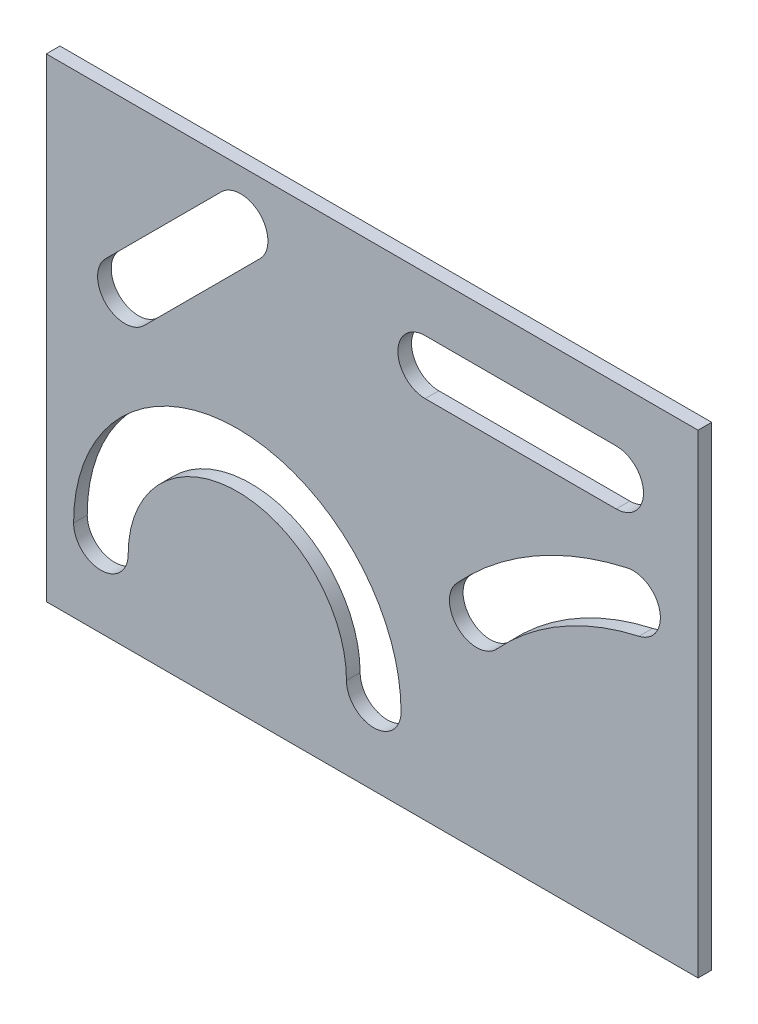
SolidWorks part; units mm, degrees
ref_plane "Front Plane" through (0, 0, 0) normal (0, 0, 1) x (1, 0, 0)
ref_plane "Top Plane" through (0, 0, 0) normal (0, 1, 0) x (1, 0, 0)
ref_plane "Right Plane" through (0, 0, 0) normal (1, 0, 0) x (0, 0, -1)
other "Configuration Table"
sketch "Sketch1" plane through (0, 0, 0) normal (0, 0, 1) x (1, 0, 0)
  line L1 (-238.8352, -173.858) -> (238.8352, -173.858)
  line L2 (-238.8352, -173.858) -> (-238.8352, 173.858)
  line L3 (-238.8352, 173.858) -> (238.8352, 173.858)
  line L4 (238.8352, -173.858) -> (238.8352, 173.858)
  line L5 (-238.8352, -173.858) -> (238.8352, 173.858) construction
  line L6 (-238.8352, 173.858) -> (238.8352, -173.858) construction
  point P0 (0, 0)
extrude "Boss-Extrude1" add sketch "Sketch1" along normal blind 10
sketch "Sketch2" plane through (0, 0, 10) normal (0, 0, 1) x (1, 0, 0)
  line L0 (-181.2616, 51.4316) -> (-96.4088, 136.2844) construction
  line L1 (-195.4037, 65.5737) -> (-110.5509, 150.4265)
  line L2 (-167.1194, 37.2894) -> (-82.2666, 122.1422)
  line L3 (38.8352, 113.858) -> (178.8352, 113.858) construction
  line L4 (38.8352, 133.858) -> (178.8352, 133.858)
  line L5 (38.8352, 93.858) -> (178.8352, 93.858)
  line L6 (238.8352, -173.858) -> (128.8352, 16.6676) construction
  line L7 (238.8352, -173.858) -> (238.8352, 173.858) construction
  line L8 (-198.8352, -113.858) -> (1.1648, -113.858) construction
  line L9 (-238.8352, 173.858) -> (-238.8352, -173.858) construction
  line L10 (-238.8352, -173.858) -> (238.8352, -173.858) construction
  line L12 (238.8352, 173.858) -> (-238.8352, 173.858) construction
  arc A0 (-195.4037, 65.5737) -> (-167.1194, 37.2894) centre (-181.2616, 51.4316) ccw
  arc A1 (-82.2666, 122.1422) -> (-110.5509, 150.4265) centre (-96.4088, 136.2844) ccw
  arc A2 (38.8352, 133.858) -> (38.8352, 93.858) centre (38.8352, 113.858) ccw
  arc A3 (178.8352, 93.858) -> (178.8352, 133.858) centre (178.8352, 113.858) ccw
  arc A4 (-198.8352, -113.858) -> (1.1648, -113.858) centre (-98.8352, -113.858) cw construction
  arc A5 (21.1648, -113.858) -> (-218.8352, -113.858) centre (-98.8352, -113.858) ccw
  arc A6 (-18.8352, -113.858) -> (-178.8352, -113.858) centre (-98.8352, -113.858) ccw
  arc A7 (-18.8352, -113.858) -> (21.1648, -113.858) centre (1.1648, -113.858) ccw
  arc A8 (-218.8352, -113.858) -> (-178.8352, -113.858) centre (-198.8352, -113.858) ccw
  arc A9 (191.2185, 40.9272) -> (76.6342, -25.2281) centre (238.8352, -173.858) ccw construction
  arc A10 (186.8897, 60.4531) -> (61.8886, -11.7163) centre (238.8352, -173.858) ccw
  arc A11 (195.5473, 21.4012) -> (91.3797, -38.7399) centre (238.8352, -173.858) ccw
  arc A12 (195.5473, 21.4012) -> (186.8897, 60.4531) centre (191.2185, 40.9272) ccw
  arc A13 (61.8886, -11.7163) -> (91.3797, -38.7399) centre (76.6342, -25.2281) ccw
  point P2 (-138.8352, 93.858)
  point P9 (108.8352, 113.858)
  point P17 (-98.8352, -13.858)
  point P26 (128.8352, 16.6676)
  dimension "D7" = 100
  dimension "D10" = 220
  dimension "D2" = 40
  dimension "D3" = 40
  dimension "D4" = 180
  dimension "D5" = 40
  dimension "D8" = 40
  dimension "D11" = 30
  dimension "D12" = 40
  dimension "D13" = 60
  dimension "D14" = 160
  dimension "D15" = 45
  dimension "D16" = 130
  dimension "D17" = 100
  dimension "D18" = 80
  dimension "D19" = 60
  dimension "D6" = 180
  dimension "D9" = 35
extrude "Cut-Extrude1" cut sketch "Sketch2" against normal blind 10
